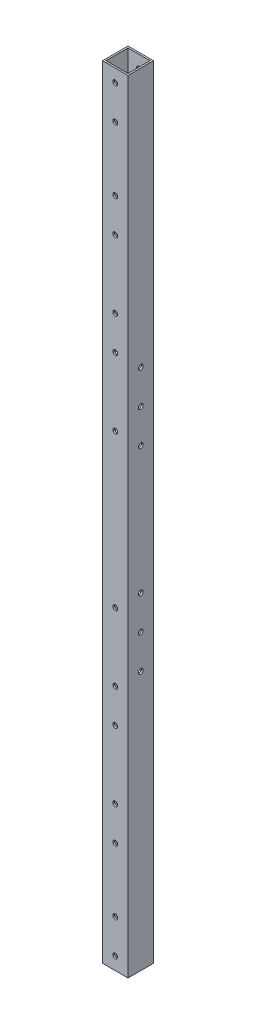
SolidWorks part; units mm, degrees
material "Thornel Mat VMA"
ref_plane "前视基准面" through (0, 0, 0) normal (0, 0, 1) x (1, 0, 0)
ref_plane "上视基准面" through (0, 0, 0) normal (0, 1, 0) x (1, 0, 0)
ref_plane "右视基准面" through (0, 0, 0) normal (1, 0, 0) x (0, 0, -1)
sketch "草图1" plane through (0, 0, 0) normal (0, 1, 0) x (1, 0, 0)
  line L1 (-7.5, -7.5) -> (7.5, -7.5)
  line L2 (-7.5, -7.5) -> (-7.5, 7.5)
  line L3 (-7.5, 7.5) -> (7.5, 7.5)
  line L4 (7.5, -7.5) -> (7.5, 7.5)
  line L5 (-7.5, -7.5) -> (7.5, 7.5) construction
  line L6 (-7.5, 7.5) -> (7.5, -7.5) construction
  point P0 (0, 0)
  dimension "D1" = 15
  dimension "D2" = 15
extrude "拉伸-薄壁1" add sketch "草图1" along normal blind 460 thin thin type one direction reverse wall 1
sketch "草图2" plane through (0, 0, 7.5) normal (0, 0, 1) x (1, 0, 0)
  line L0 (0, 0) -> (0, 460) construction
  line L1 (-7.5, 460) -> (7.5, 460) construction
  line L2 (-1000, 230) -> (49000, 230) construction
  line L3 (-7.5, 0) -> (7.5, 0) construction
  circle A0 centre (0, 7.5) radius 1.45
  circle A1 centre (0, 27.5) radius 1.45
  circle A2 centre (0, 432.5) radius 1.45
  circle A3 centre (0, 452.5) radius 1.45
  circle A4 centre (0, 65) radius 1.45
  circle A5 centre (0, 85) radius 1.45
  circle A6 centre (0, 125) radius 1.45
  circle A7 centre (0, 145) radius 1.45
  circle A8 centre (0, 315) radius 1.45
  circle A9 centre (0, 335) radius 1.45
  circle A10 centre (0, 375) radius 1.45
  circle A11 centre (0, 395) radius 1.45
  circle A12 centre (0, 185) radius 1.45
  circle A13 centre (0, 275) radius 1.45
  point P8 (0, 230)
  dimension "D1" = 2.9
  dimension "D4" = 85
  dimension "D5" = 20
  dimension "D6" = 40
  dimension "D7" = 20
  dimension "D8" = 40
  dimension "D2" = 7.5
  dimension "D3" = 20
extrude "切除-拉伸1" cut sketch "草图2" against normal through all
sketch "草图3" plane through (7.5, 0, 0) normal (1, 0, 0) x (0, 0, -1)
  line L0 (0, 0) -> (0, 460) construction
  line L1 (-7.5, 460) -> (7.5, 460) construction
  line L2 (-1000, 230) -> (49000, 230) construction
  circle A0 centre (0, 152.5) radius 1.45
  circle A1 centre (0, 172.5) radius 1.45
  circle A2 centre (0, 287.5) radius 1.45
  circle A3 centre (0, 307.5) radius 1.45
  circle A4 centre (0, 192.5) radius 1.45
  circle A5 centre (0, 267.5) radius 1.45
  point P12 (0, 230)
  dimension "D3" = 2.9
  dimension "D1" = 20
  dimension "D2" = 20
  dimension "D4" = 115
extrude "切除-拉伸2" cut sketch "草图3" against normal through all
